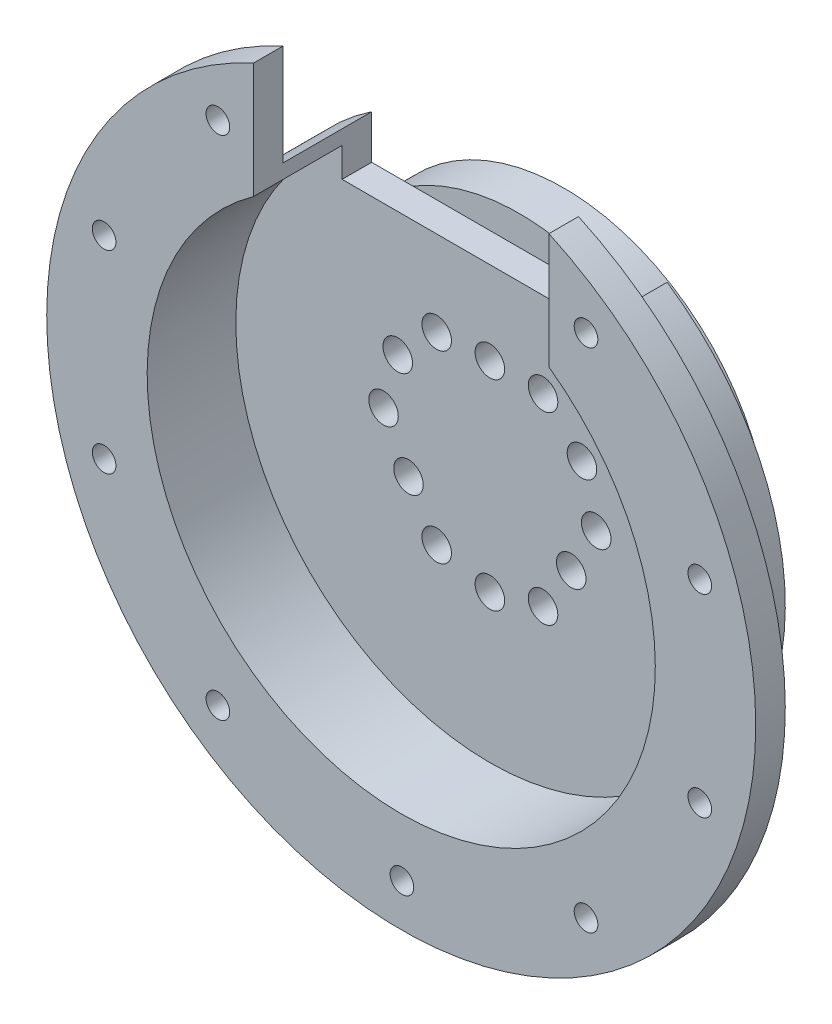
SolidWorks part; units mm, degrees
material "6061 Alloy"
ref_plane "Front Plane" through (0, 0, 0) normal (0, 0, 1) x (1, 0, 0)
ref_plane "Top Plane" through (0, 0, 0) normal (0, 1, 0) x (1, 0, 0)
ref_plane "Right Plane" through (0, 0, 0) normal (1, 0, 0) x (0, 0, -1)
sketch "Sketch1" plane through (0, 0, 0) normal (0, 0, 1) x (1, 0, 0)
  circle A0 centre (0, 0) radius 45
  dimension "D1" = 90
extrude "Boss-Extrude1" add sketch "Sketch1" along normal blind 5
sketch "Sketch2" plane through (0, 0, 5) normal (0, 0, 1) x (1, 0, 0)
  circle A16 centre (0, 0) radius 15.9 construction
  circle A17 centre (0, 0) radius 18 construction
  circle A18 centre (0, 15.9) radius 2.5
  circle A19 centre (13.7698, -7.95) radius 2.5
  circle A20 centre (-13.7698, -7.95) radius 2.5
  arc A21 (0, 18) -> (9, 15.5885) centre (0, 0) cw construction
  circle A22 centre (9, 15.5885) radius 2.5
  circle A23 centre (15.5885, 9) radius 2.5
  circle A24 centre (18, 0) radius 2.5
  circle A25 centre (9, -15.5885) radius 2.5
  circle A26 centre (0, -18) radius 2.5
  circle A27 centre (-9, -15.5885) radius 2.5
  circle A28 centre (-18, 0) radius 2.5
  circle A29 centre (-15.5885, 9) radius 2.5
  circle A30 centre (-9, 15.5885) radius 2.5
  point P12 (0, 0)
  point P20 (0, 0)
  point P33 (0, 0)
  dimension "D1" = 31.8
  dimension "D2" = 3
  dimension "D3" = 3
  dimension "D4" = 3
extrude "Cut-Extrude1" cut sketch "Sketch2" against normal blind 5
sketch "Sketch3" plane through (0, 0, 5) normal (0, 0, 1) x (1, 0, 0)
  circle A0 centre (0, 0) radius 43
  circle A1 centre (0, 0) radius 45
  dimension "D1" = 90
  dimension "D2" = 86
extrude "Boss-Extrude2" add sketch "Sketch3" along normal blind 10
sketch "Sketch4" plane through (0, 0, 15) normal (0, 0, 1) x (1, 0, 0)
  circle A0 centre (0, 0) radius 43
  circle A1 centre (0, 0) radius 60
  dimension "D1" = 86
extrude "Boss-Extrude3" add sketch "Sketch4" along normal blind 5
sketch "Sketch5" plane through (0, 0, 20) normal (0, 0, 1) x (1, 0, 0)
  circle A0 centre (0, 0) radius 59.8066 construction
  circle A2 centre (0, 0) radius 53 construction
  circle A3 centre (0, 53) radius 2
  circle A4 centre (31.2742, 43.1431) radius 2
  circle A5 centre (50.5276, 16.6431) radius 2
  circle A6 centre (50.5276, -16.1127) radius 2
  circle A7 centre (31.2742, -42.6127) radius 2
  circle A8 centre (0.1216, -52.7348) radius 2
  circle A9 centre (-31.031, -42.6127) radius 2
  circle A10 centre (-50.2844, -16.1127) radius 2
  circle A11 centre (-50.2844, 16.6431) radius 2
  circle A12 centre (-31.031, 43.1431) radius 2
  point P30 (0, 0)
  dimension "D1" = 106
  dimension "D2" = 4
extrude "Cut-Extrude2" cut sketch "Sketch5" against normal blind 5
sketch "Sketch6" plane through (0, 0, 0) normal (0, 1, 0) x (1, 0, 0)
  line L1 (60, -15) -> (-60, -15) construction
  line L2 (-25, -15) -> (-25, 5)
  line L3 (-25, 5) -> (25, 5)
  line L4 (25, 5) -> (25, -15)
  line L7 (-25, -15) -> (-25, -26.8126)
  line L8 (-25, -26.8126) -> (25, -26.8126)
  line L9 (25, -26.8126) -> (25, -15)
  dimension "D1" = 20
extrude "Cut-Extrude3" cut sketch "Sketch6" along normal blind 81 from offset 30
sketch "Sketch7" plane through (0, 0, 0) normal (0, 0, -1) x (-1, 0, 0)
  circle A0 centre (-15.5885, 9) radius 2.5 construction
  circle A1 centre (-18, 0) radius 2.5 construction
  circle A2 centre (-13.7698, -7.95) radius 2.5 construction
  circle A3 centre (-9, -15.5885) radius 2.5 construction
  circle A4 centre (0, -18) radius 2.5 construction
  circle A5 centre (9, -15.5885) radius 2.5 construction
  circle A6 centre (13.7698, -7.95) radius 2.5 construction
  circle A7 centre (18, 0) radius 2.5 construction
  circle A8 centre (15.5885, 9) radius 2.5 construction
  circle A9 centre (9, 15.5885) radius 2.5 construction
  circle A10 centre (0, 15.9) radius 2.5 construction
  circle A11 centre (-9, 15.5885) radius 2.5 construction
  circle A12 centre (-15.5885, 9) radius 2.5
  circle A13 centre (-18, 0) radius 2.5
  circle A14 centre (-13.7698, -7.95) radius 2.5
  circle A15 centre (-9, -15.5885) radius 2.5
  circle A16 centre (0, -18) radius 2.5
  circle A17 centre (9, -15.5885) radius 2.5
  circle A18 centre (13.7698, -7.95) radius 2.5
  circle A19 centre (18, 0) radius 2.5
  circle A20 centre (15.5885, 9) radius 2.5
  circle A21 centre (9, 15.5885) radius 2.5
  circle A22 centre (0, 15.9) radius 2.5
  circle A23 centre (-9, 15.5885) radius 2.5
  circle A24 centre (0, 0) radius 35
extrude "Boss-Extrude4" add sketch "Sketch7" along normal blind 7.5
sketch "Sketch8" plane through (0, 0, 15) normal (0, 0, -1) x (-1, 0, 0)
  line L0 (-59.9908, -1.0485) -> (-44.9923, -0.8303)
  line L3 (-13.9788, -42.7738) -> (-18.6749, -57.0197)
  arc A0 (-25, 37.4166) -> (25, 37.4166) centre (0, 0) ccw construction
  arc A1 (-25, 54.5436) -> (25, 54.5436) centre (0, 0) ccw construction
  arc A2 (-59.9908, -1.0485) -> (-18.6749, -57.0197) centre (0, 0) ccw
  arc A3 (-44.9923, -0.8303) -> (-13.9788, -42.7738) centre (0, 0) ccw
  arc A4 (-59.9908, -1.0485) -> (-18.6749, -57.0197) centre (0, 0) ccw
  arc A5 (-44.9923, -0.8303) -> (-13.9788, -42.7738) centre (0, 0) ccw
  circle A6 centre (-50.5276, -16.1127) radius 2
  circle A7 centre (-31.2742, -42.6127) radius 2
